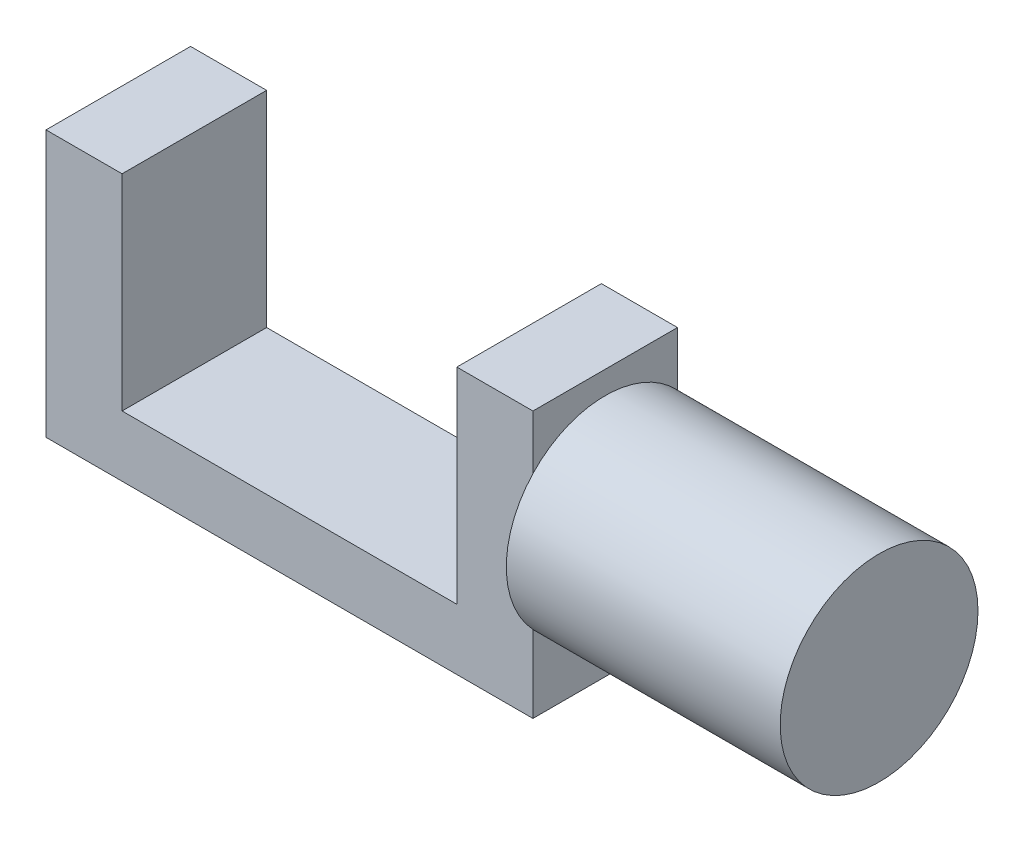
SolidWorks part; units mm, degrees
ref_plane "前视基准面" through (0, 0, 0) normal (0, 0, 1) x (1, 0, 0)
ref_plane "上视基准面" through (0, 0, 0) normal (0, 1, 0) x (1, 0, 0)
ref_plane "右视基准面" through (0, 0, 0) normal (1, 0, 0) x (0, 0, -1)
sketch "草图1" plane through (0, 0, 0) normal (0, 1, 0) x (1, 0, 0)
  line L1 (0, 0) -> (32, 0)
  line L2 (0, 0) -> (0, -9.5)
  line L3 (0, -9.5) -> (32, -9.5)
  line L4 (32, 0) -> (32, -9.5)
  dimension "D1" = 32
  dimension "D2" = 9.5
extrude "凸台-拉伸1" add sketch "草图1" along normal blind 4
sketch "草图2" plane through (0, 4, 0) normal (0, 1, 0) x (1, 0, 0)
  line L0 (0, -9.5) -> (32, -9.5) construction
  line L1 (0, 0) -> (5, 0)
  line L2 (0, 0) -> (0, -9.5)
  line L3 (0, -9.5) -> (5, -9.5)
  line L4 (5, 0) -> (5, -9.5)
  dimension "D1" = 5
extrude "凸台-拉伸2" add sketch "草图2" along normal blind 13.5
sketch "草图3" plane through (0, 4, 0) normal (0, 1, 0) x (1, 0, 0)
  line L0 (5, -9.5) -> (32, -9.5) construction
  line L1 (32, 0) -> (27, 0)
  line L2 (32, 0) -> (32, -9.5)
  line L3 (32, -9.5) -> (27, -9.5)
  line L4 (27, 0) -> (27, -9.5)
  dimension "D1" = 5
extrude "凸台-拉伸3" add sketch "草图3" along normal blind 13.5
sketch "草图4" plane through (32, 0, 0) normal (1, 0, 0) x (0, 0, -1)
  line L0 (-4.75, 9.5) -> (-9.5, 9.5) construction
  line L1 (-9.5, 17.5) -> (-9.5, 0) construction
  line L2 (-4.75, 9.5) -> (0, 9.5) construction
  line L3 (0, 17.5) -> (0, 0) construction
  line L4 (-4.75, 9.5) -> (-4.75, 0) construction
  line L5 (-9.5, 0) -> (0, 0) construction
  line L6 (-4.75, 9.5) -> (-4.75, 17.5) construction
  line L7 (-9.5, 17.5) -> (0, 17.5) construction
  circle A0 centre (-4.75, 9.5) radius 6.5
  dimension "D1" = 13
  dimension "D2" = 8
  dimension "D3" = 9.5
extrude "凸台-拉伸4" add sketch "草图4" along normal blind 18
